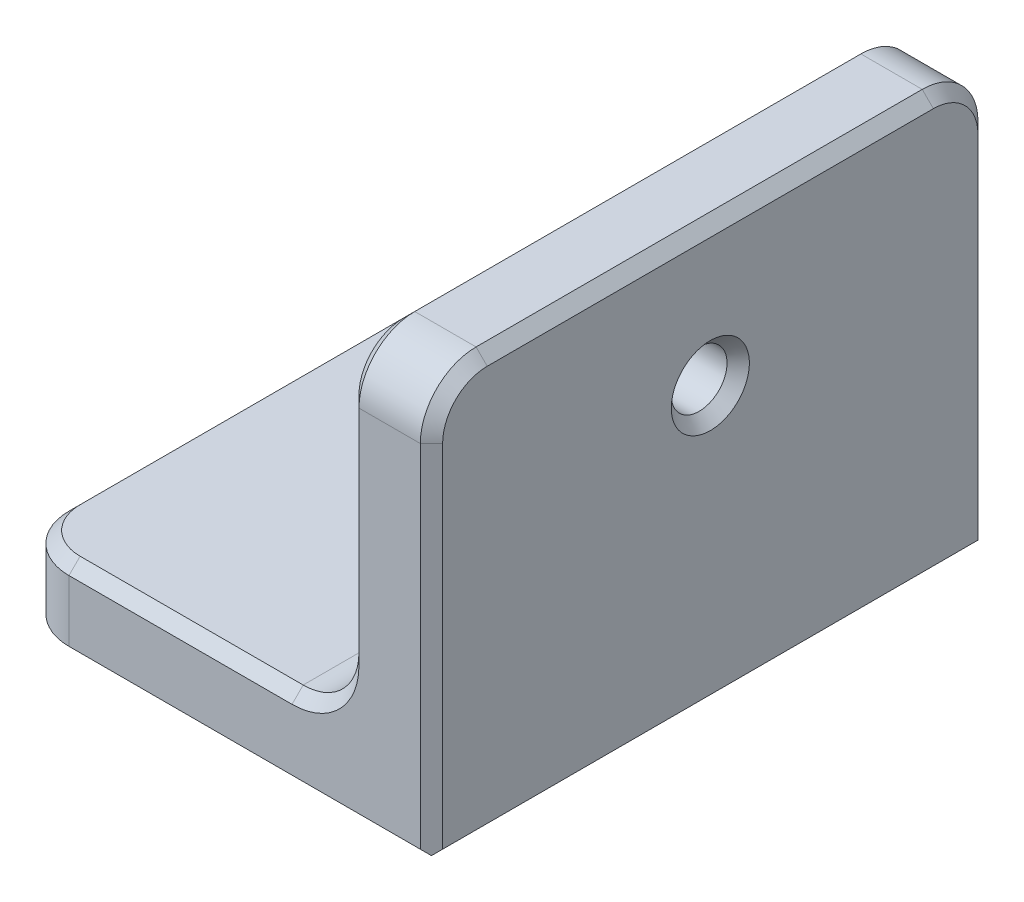
SolidWorks part; units mm, degrees
ref_plane "前视基准面" through (0, 0, 0) normal (0, 0, 1) x (1, 0, 0)
ref_plane "上视基准面" through (0, 0, 0) normal (0, 1, 0) x (1, 0, 0)
ref_plane "右视基准面" through (0, 0, 0) normal (1, 0, 0) x (0, 0, -1)
other "Configuration Table"
sketch "草图1" plane through (0, 0, 0) normal (0, 1, 0) x (1, 0, 0)
  line L1 (0, 0) -> (15, 0)
  line L2 (0, 0) -> (0, 20)
  line L3 (0, 20) -> (15, 20)
  line L4 (15, 0) -> (15, 20)
  dimension "D1" = 20
  dimension "D2" = 15
extrude "凸台-拉伸1" add sketch "草图1" along normal blind 3
sketch "草图2" plane through (0, 3, 0) normal (0, 1, 0) x (1, 0, 0)
  line L0 (0, 20) -> (0, 0) construction
  line L1 (0, 0) -> (15, 0) construction
  circle A0 centre (5.5, 10) radius 1.6
  point P4 (0, 10)
  point P5 (7.5, 0)
  point P7 (7.3716, 6.5652)
  dimension "D1" = 3.2
  dimension "D3" = 2
  dimension "D2" = 0
extrude "切除-拉伸1" cut sketch "草图2" against normal blind 3
sketch "草图3" plane through (0, 3, 0) normal (0, 1, 0) x (1, 0, 0)
  line L0 (0, 0) -> (15, 0) construction
  line L1 (15, 20) -> (12, 20)
  line L2 (15, 20) -> (15, 0)
  line L3 (15, 0) -> (12, 0)
  line L4 (12, 20) -> (12, 0)
  dimension "D1" = 3
extrude "凸台-拉伸2" add sketch "草图3" along normal blind 12
fillet "圆角1" radius 2 1 edges at (12, 3, -10)
sketch "草图4" plane through (12, 0, 0) normal (-1, 0, 0) x (0, 0, 1)
  line L0 (-20, 15) -> (0, 15) construction
  line L1 (0, 15) -> (0, 5) construction
  circle A0 centre (-10, 10) radius 1
  point P4 (-10, 15)
  point P7 (0, 10)
  dimension "D1" = 2
  dimension "D2" = 0
  dimension "D3" = 0
extrude "切除-拉伸2" cut sketch "草图4" against normal blind 10
fillet "圆角2" radius 2 4 edges at (13.5, 15, -20) (13.5, 15, 0) (0, 1.5, 0) (0, 1.5, -20)
chamfer "倒角1" distance 0.4 angle 45 7 edges at (15, 0, -10) (8.5, 0, -20) (0.5858, 0, -19.4142) (0, 0, -10) (0.5858, 0, -0.5858) (8.5, 0, 0) (5.5, 0, -8.4)
chamfer "倒角2" distance 0.4 angle 45 5 edges at (15, 6.7, -20) (15, 14.4142, -19.4142) (15, 15, -10) (15, 14.4142, -0.5858) (15, 6.7, 0)
chamfer "倒角3" distance 0.4 angle 45 14 edges at (15, 10, -9) (12, 10, -9) (6, 3, 0) (11.4142, 3.5858, 0) (0.5858, 3, -0.5858) (12, 9, 0) (0, 3, -10) (12, 14.4142, -0.5858) (0.5858, 3, -19.4142) (12, 15, -10) (6, 3, -20) (12, 14.4142, -19.4142) (11.4142, 3.5858, -20) (12, 9, -20)
